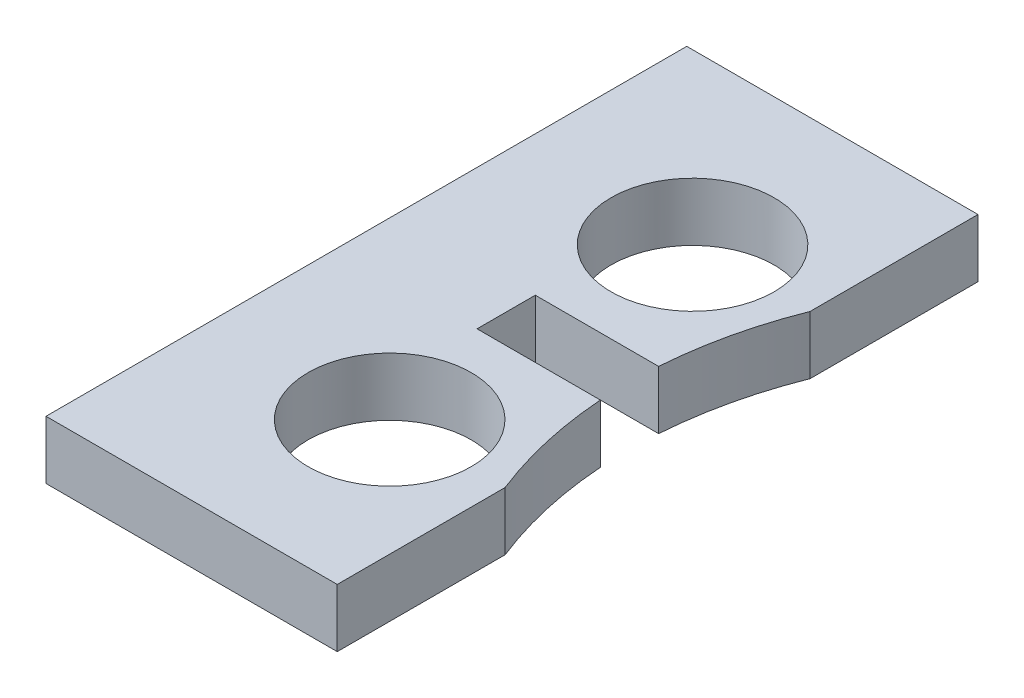
SolidWorks part; units mm, degrees
ref_plane "Front Plane" through (0, 0, 0) normal (0, 0, 1) x (1, 0, 0)
ref_plane "Top Plane" through (0, 0, 0) normal (0, 1, 0) x (1, 0, 0)
ref_plane "Right Plane" through (0, 0, 0) normal (1, 0, 0) x (0, 0, -1)
sketch "Sketch2" plane through (0, 0, 0) normal (0, 0, 1) x (1, 0, 0)
  line L1 (0, 0) -> (25, 0)
  line L2 (0, 0) -> (0, 5)
  line L3 (0, 5) -> (25, 5)
  line L4 (25, 0) -> (25, 5)
  line L5 (5, 0) -> (25, 0)
  line L6 (5, 0) -> (5, 5)
  line L7 (5, 5) -> (25, 5)
  line L8 (25, 0) -> (25, 5)
  dimension "D1" = 25
  dimension "D2" = 5
  dimension "D3" = 20
extrude "Boss-Extrude2" add sketch "Sketch2" along normal blind 25 contours L6 L1 L4 L3
sketch "Sketch3" plane through (0, 0, 0) normal (0, 0, -1) x (-1, 0, 0)
  line L1 (-25, 0) -> (0, 0)
  line L2 (-25, 0) -> (-25, 5)
  line L3 (-25, 5) -> (0, 5)
  line L4 (0, 0) -> (0, 5)
  line L5 (-5, 0) -> (0, 0)
  line L6 (-5, 0) -> (-5, 5)
  line L7 (-5, 5) -> (0, 5)
  line L8 (0, 0) -> (0, 5)
  line M1 (-5, 0) -> (-5, 5)
  dimension "D1" = 25
  dimension "D2" = 5
extrude "Boss-Extrude3" add sketch "Sketch3" along normal blind 5 and the other way blind 25 contours L1 L4 L3 M1
sketch "Sketch4" plane through (0, 0, -5) normal (0, 0, -1) x (-1, 0, 0)
  line L1 (0, 0) -> (-25, 0)
  line L2 (0, 0) -> (0, 5)
  line L3 (0, 5) -> (-25, 5)
  line L4 (-25, 0) -> (-25, 5)
  dimension "D1" = 25
  dimension "D2" = 5
extrude "Boss-Extrude4" add sketch "Sketch4" along normal blind 25
sketch "Sketch5" plane through (0, 5, 0) normal (0, 1, 0) x (1, 0, 0)
  line L1 (25, 30) -> (25, 5) construction
  line L2 (25, -25) -> (25, 0) construction
  line L5 (5, 5) -> (25, 5) construction
  circle A0 centre (15, -10.5) radius 7
  circle A1 centre (15, 15.5) radius 7
  dimension "D1" = 14
  dimension "D2" = 14
  dimension "D3" = 26
  dimension "D4" = 10
  dimension "D5" = 10
  dimension "D6" = 10.5
extrude "Cut-Extrude1" cut sketch "Sketch5" against normal blind 30
sketch "Sketch6" plane through (0, 0, 0) normal (0, -1, 0) x (1, 0, 0)
  line L0 (5, -2.5) -> (58, -2.5)
  line L1 (5, 0) -> (5, -5) construction
  circle A0 centre (58, -2.5) radius 35.5
  line M3 (5, 0) -> (25, 0)
  line M4 (25, 0) -> (25, 25)
  line M8 (25, -30) -> (25, -5)
  line M9 (25, -5) -> (5, -5)
  dimension "D2" = 71
  dimension "D1" = 53
extrude "Cut-Extrude2" cut sketch "Sketch6" against normal blind 10 contours A0 M9 M8 | A0 M4 M3
sketch "Sketch7" plane through (5, 0, 0) normal (1, 0, 0) x (0, 0, -1)
  line L1 (5, 5) -> (0, 5)
  line L2 (5, 5) -> (5, 0)
  line L3 (5, 0) -> (0, 0)
  line L4 (0, 5) -> (0, 0)
extrude "Boss-Extrude5" add sketch "Sketch7" along normal blind 7
